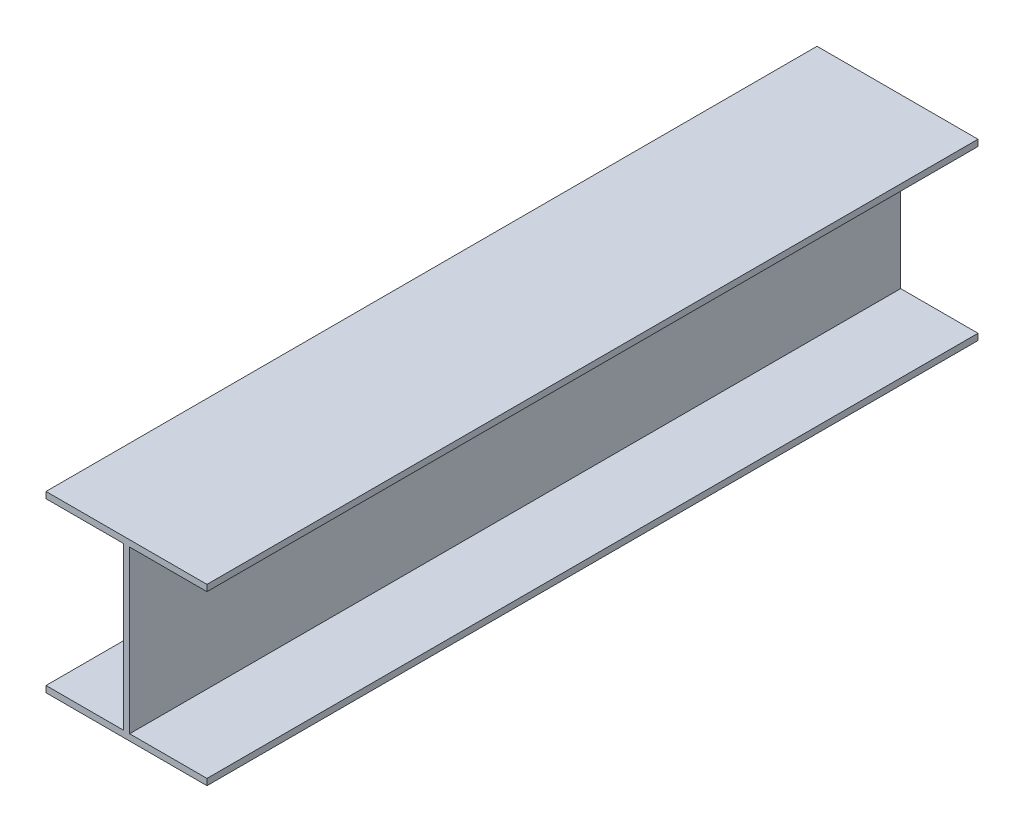
SolidWorks part; units mm, degrees
ref_plane "Front Plane" through (0, 0, 0) normal (0, 0, 1) x (1, 0, 0)
ref_plane "Top Plane" through (0, 0, 0) normal (0, 1, 0) x (1, 0, 0)
ref_plane "Right Plane" through (0, 0, 0) normal (1, 0, 0) x (0, 0, -1)
sketch "Sketch1" plane through (0, 0, 0) normal (0, 0, 1) x (1, 0, 0)
  line L1 (-76.2, 82.55) -> (76.2, 82.55)
  line L2 (-76.2, 76.55) -> (-3, 76.55)
  line L3 (-76.2, -82.55) -> (76.2, -82.55) construction
  line L4 (-76.2, -76.55) -> (-3, -76.55)
  line L5 (-76.2, 82.55) -> (-70.6615, 76.55) construction
  line L6 (-76.2, -82.55) -> (-70.6615, -76.55) construction
  line L7 (-3, 76.55) -> (-3, -76.55)
  line L8 (3, 76.55) -> (3, -76.55)
  line L9 (-76.2, 82.55) -> (-76.2, 76.55)
  line L10 (-76.2, 76.55) -> (-76.1941, 76.5423)
  line L11 (76.2, 82.55) -> (76.2, 76.55)
  line L12 (-76.2, -76.55) -> (-76.2, -82.55)
  line L13 (-76.2, -82.55) -> (76.2, -82.55)
  line L14 (76.2, -82.55) -> (76.2, -76.55)
  line L16 (70.6615, 76.55) -> (76.2, 82.55) construction
  line L17 (70.6615, -76.55) -> (76.2, -82.55) construction
  line L18 (3, 76.55) -> (76.2, 76.55)
  line L19 (-76.2, 76.55) -> (76.2, 76.55) construction
  line L20 (3, -76.55) -> (76.2, -76.55)
  line L21 (-76.2, -76.55) -> (76.2, -76.55) construction
  point P0 (0, 0)
  dimension "D1" = 165.1
  dimension "D2" = 152.4
extrude "Boss-Extrude1" add sketch "Sketch1" along normal blind 730 contours L20 L8 L18 L11 L1 L9 L2 L7 L4 L12 L13 L14
